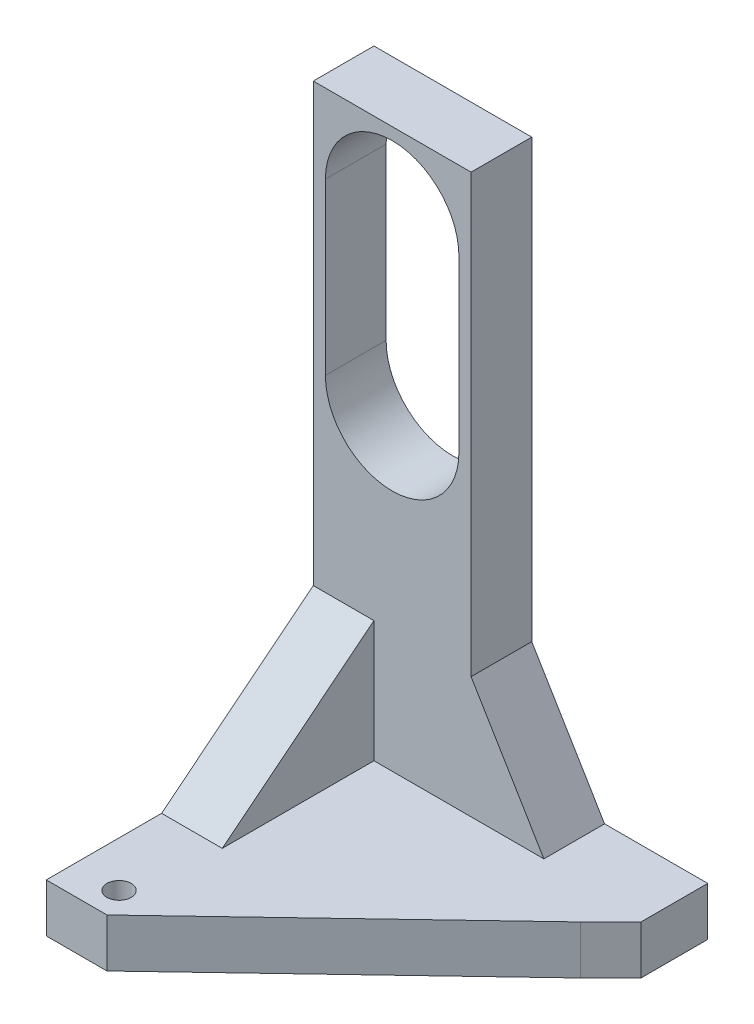
SolidWorks part; units mm, degrees
ref_plane "前视基准面" through (0, 0, 0) normal (0, 0, 1) x (1, 0, 0)
ref_plane "上视基准面" through (0, 0, 0) normal (0, 1, 0) x (1, 0, 0)
ref_plane "右视基准面" through (0, 0, 0) normal (1, 0, 0) x (0, 0, -1)
other "Configuration Table"
sketch "草图2" plane through (0, 0, 0) normal (0, 0, 1) x (1, 0, 0)
  line L0 (13, -58.75) -> (-13, -58.75)
  line L1 (-13, -58.75) -> (-13, 38.25)
  line L2 (13, -58.75) -> (13, 38.25)
  line L3 (-13, 38.25) -> (13, 38.25)
  dimension "D3" = 26
extrude "凸台-拉伸1" add sketch "草图2" along normal blind 10 contours L1 L3 L2 L0
sketch "草图3" plane through (0, 0, 0) normal (0, 0, 1) x (1, 0, 0)
  line L0 (-11, -2.75) -> (-11, 25.25)
  line L3 (11, -2.75) -> (11, 25.25)
  arc A2 (-11, -2.75) -> (11, -2.75) centre (0, -2.75) ccw
  arc A3 (-11, 25.25) -> (11, 25.25) centre (0, 25.25) cw
  point P5 (0, 17.25)
  point P7 (0, 17.25)
extrude "切除-拉伸11" cut sketch "草图3" along normal blind 10
sketch3d "3D草图1"
  point P0 (4.6572, -58.75, 5.0982)
ref_plane "基准面1" through (0, -58.75, 0) normal (0, -1, 0) x (1, 0, 0)
sketch "草图4" plane through (0, -58.75, 0) normal (0, -1, 0) x (1, 0, 0)
  line L1 (-13, 0) -> (37, 0)
  line L2 (-13, 0) -> (-13, 54)
  line L3 (37, 0) -> (37, 16)
  line L4 (-13, 54) -> (-3, 54)
  line L5 (-3, 54) -> (37, 16)
extrude "凸台-拉伸2" add sketch "草图4" along normal blind 3
sketch3d "3D草图2"
  point P0 (-13, -28.4592, 5.552)
ref_plane "基准面2" through (-13, 0, 0) normal (-1, 0, 0) x (0, 0, 1)
sketch3d "3D草图3"
  point P0 (7.2288, -38.9654, 0)
ref_plane "基准面3" through (0, 0, 0) normal (0, 0, -1) x (-1, 0, 0)
sketch3d "3D草图4"
  point P0 (-1.7674, -61.75, 13.3752)
ref_plane "基准面4" through (0, -61.75, 0) normal (0, -1, 0) x (1, 0, 0)
sketch "草图8" plane through (0, -61.75, 0) normal (0, -1, 0) x (1, 0, 0)
  circle A0 centre (-5.5, 49.5) radius 2
extrude "切除-拉伸12" cut sketch "草图8" against normal blind 3
sketch "草图9" plane through (0, -58.75, 0) normal (0, 1, 0) x (1, 0, 0)
  line L0 (-13, -10) -> (-13, -54)
  line L1 (-13, -54) -> (-3, -54)
  line L2 (-3, -54) -> (37, -16)
  line L3 (37, -16) -> (37, 0)
  line L4 (37, 0) -> (13, 0)
  line L5 (13, 0) -> (13, -10)
  line L6 (13, -10) -> (-13, -10)
extrude "凸台-拉伸3" add sketch "草图9" along normal blind 5
sketch "草图10" plane through (0, -53.75, 0) normal (0, 1, 0) x (1, 0, 0)
  circle A0 centre (-5.5, -49.5) radius 2
extrude "切除-拉伸13" cut sketch "草图10" against normal blind 10 contours A0
sketch "草图11" plane through (0, 0, 0) normal (0, 0, -1) x (-1, 0, 0)
  line L2 (-13, -53.75) -> (-13, 38.25) construction
  line L3 (-13, -33.75) -> (-13, -53.75)
  line L8 (-13, -53.75) -> (-25, -53.75)
  line L9 (-37, -53.75) -> (-13, -53.75) construction
  line L10 (-13, -33.75) -> (-25, -53.75)
extrude "凸台-拉伸4" add sketch "草图11" against normal blind 10
sketch "草图12" plane through (-13, 0, 0) normal (-1, 0, 0) x (0, 0, 1)
  line L0 (10, -53.75) -> (35, -53.75)
  line L1 (10, -53.75) -> (54, -53.75) construction
  line L3 (10, -53.75) -> (10, 38.25) construction
  line L4 (10, -33.75) -> (10, -53.75)
  line L5 (10, -33.75) -> (35, -53.75)
extrude "凸台-拉伸5" add sketch "草图12" against normal blind 10
sketch "草图13" plane through (0, -53.75, 0) normal (0, 1, 0) x (1, 0, 0)
  line L0 (37, 0) -> (42, 0)
  line L1 (37, -16) -> (42, -11)
  line L2 (42, -11) -> (42, 0)
  line L3 (37, 0) -> (37, -16)
extrude "凸台-拉伸6" add sketch "草图13" against normal blind 8 contours L2 L0 L3 L1
